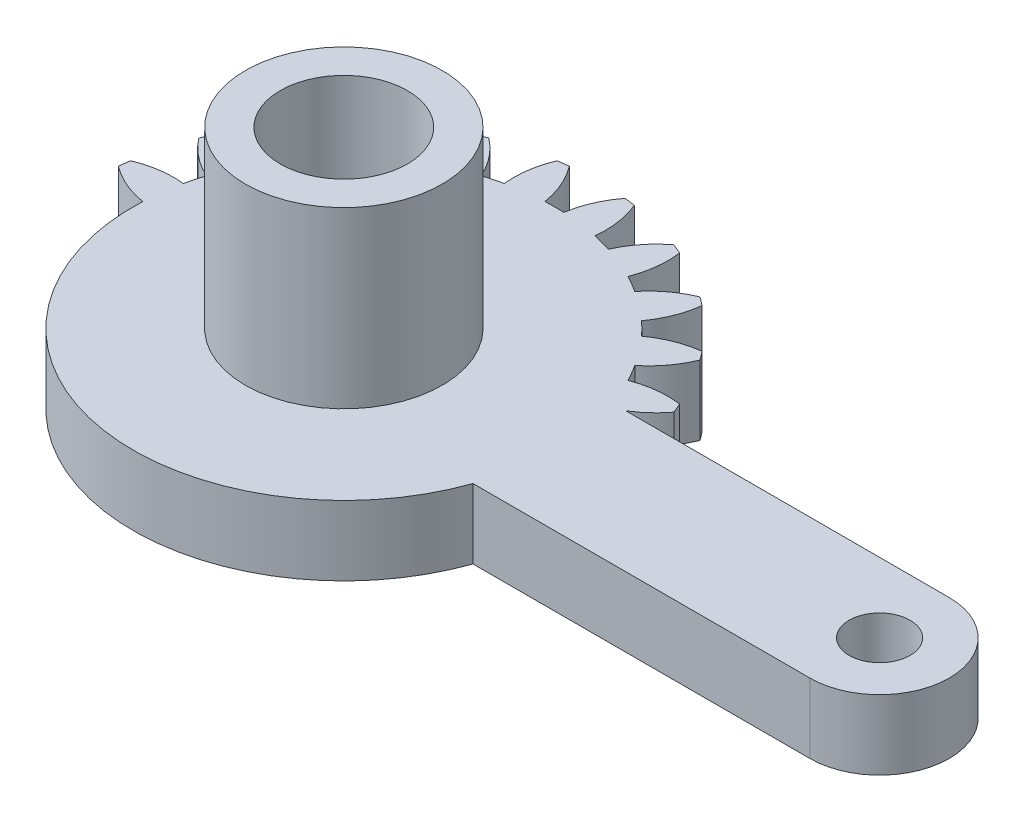
SolidWorks part; units mm, degrees
ref_plane "Front Plane" through (0, 0, 0) normal (0, 0, 1) x (1, 0, 0)
ref_plane "Top Plane" through (0, 0, 0) normal (0, 1, 0) x (1, 0, 0)
ref_plane "Right Plane" through (0, 0, 0) normal (1, 0, 0) x (0, 0, -1)
ref_plane "Plane1" through (0, 4, 0) normal (0, 1, 0) x (1, 0, 0)
sketch "Sketch1" plane through (0, 4, 0) normal (0, 1, 0) x (1, 0, 0)
  line L0 (1.3057, -4) -> (20.6437, -4)
  line L1 (20.6437, 4) -> (2.0816, 4)
  arc A0 (-24.5622, 2.2179) -> (-24.6437, 1.5991) centre (-10.1063, 0) ccw
  arc A1 (-24.6437, 1.5991) -> (-22.1869, 0.5427) centre (-21.3486, 5.8773) ccw
  arc A2 (-22.1869, 0.5427) -> (1.3057, -4) centre (-10.1063, 0) ccw
  arc A3 (20.6437, -4) -> (20.6437, 4) centre (20.6437, 0) ccw
  arc A4 (2.0816, 4) -> (3.5217, 5.3071) centre (-0.7683, 8.5867) ccw
  arc A5 (3.5217, 5.3071) -> (3.2829, 5.8838) centre (-10.1063, 0) ccw
  arc A6 (3.2829, 5.8838) -> (0.6271, 5.5703) centre (2.5684, 0.5313) ccw
  arc A7 (0.6271, 5.5703) -> (0.0844, 6.5103) centre (-10.1063, 0) ccw
  arc A8 (0.0844, 6.5103) -> (1.6838, 8.6535) centre (-3.3089, 10.711) ccw
  arc A9 (1.6838, 8.6535) -> (1.3038, 9.1487) centre (-10.1063, 0) ccw
  arc A10 (1.3038, 9.1487) -> (-1.1803, 8.1585) centre (1.999, 3.7936) ccw
  arc A11 (-1.1803, 8.1585) -> (-1.9479, 8.926) centre (-10.1063, 0) ccw
  arc A12 (-1.9479, 8.926) -> (-0.9576, 11.4102) centre (-6.3127, 12.1053) ccw
  arc A13 (-0.9576, 11.4102) -> (-1.4528, 11.7901) centre (-10.1063, 0) ccw
  arc A14 (-1.4528, 11.7901) -> (-3.596, 10.1907) centre (0.6046, 6.7975) ccw
  arc A15 (-3.596, 10.1907) -> (-4.5361, 10.7334) centre (-10.1063, 0) ccw
  arc A16 (-4.5361, 10.7334) -> (-4.2225, 13.3892) centre (-9.5751, 12.6747) ccw
  arc A17 (-4.2225, 13.3892) -> (-4.7992, 13.6281) centre (-10.1063, 0) ccw
  arc A18 (-4.7992, 13.6281) -> (-6.4554, 11.5285) centre (-1.5196, 9.3381) ccw
  arc A19 (-6.4554, 11.5285) -> (-7.5039, 11.8094) centre (-10.1063, 0) ccw
  arc A20 (-7.5039, 11.8094) -> (-7.8884, 14.4558) centre (-12.8736, 12.3803) ccw
  arc A21 (-7.8884, 14.4558) -> (-8.5072, 14.5373) centre (-10.1063, 0) ccw
  arc A22 (-8.5072, 14.5373) -> (-9.5636, 12.0806) centre (-4.2291, 11.2423) ccw
  arc A23 (-9.5636, 12.0806) -> (-10.6491, 12.0806) centre (-10.1063, 0) ccw
  arc A24 (-10.6491, 12.0806) -> (-11.7054, 14.5373) centre (-15.9836, 11.2423) ccw
  arc A25 (-11.7054, 14.5373) -> (-12.3243, 14.4558) centre (-10.1063, 0) ccw
  arc A26 (-12.3243, 14.4558) -> (-12.7088, 11.8094) centre (-7.3391, 12.3803) ccw
  arc A27 (-12.7088, 11.8094) -> (-13.7573, 11.5285) centre (-10.1063, 0) ccw
  arc A28 (-13.7573, 11.5285) -> (-15.4135, 13.6281) centre (-18.6931, 9.3381) ccw
  arc A29 (-15.4135, 13.6281) -> (-15.9901, 13.3892) centre (-10.1063, 0) ccw
  arc A30 (-15.9901, 13.3892) -> (-15.6766, 10.7334) centre (-10.6376, 12.6747) ccw
  arc A31 (-15.6766, 10.7334) -> (-16.6166, 10.1907) centre (-10.1063, 0) ccw
  arc A32 (-16.6166, 10.1907) -> (-18.7599, 11.7901) centre (-20.8173, 6.7975) ccw
  arc A33 (-18.7599, 11.7901) -> (-19.255, 11.4102) centre (-10.1063, 0) ccw
  arc A34 (-19.255, 11.4102) -> (-18.2648, 8.926) centre (-13.9, 12.1053) ccw
  arc A35 (-18.2648, 8.926) -> (-19.0324, 8.1585) centre (-10.1063, 0) ccw
  arc A36 (-19.0324, 8.1585) -> (-21.5165, 9.1487) centre (-22.2117, 3.7936) ccw
  arc A37 (-21.5165, 9.1487) -> (-21.8965, 8.6535) centre (-10.1063, 0) ccw
  arc A38 (-21.8965, 8.6535) -> (-20.2971, 6.5103) centre (-16.9038, 10.711) ccw
  arc A39 (-20.2971, 6.5103) -> (-20.8398, 5.5703) centre (-10.1063, 0) ccw
  arc A40 (-20.8398, 5.5703) -> (-23.4956, 5.8838) centre (-22.7811, 0.5313) ccw
  arc A41 (-23.4956, 5.8838) -> (-23.7344, 5.3071) centre (-10.1063, 0) ccw
  arc A42 (-23.7344, 5.3071) -> (-21.6348, 3.6509) centre (-19.4444, 8.5867) ccw
  arc A43 (-21.6348, 3.6509) -> (-21.9157, 2.6025) centre (-10.1063, 0) ccw
  arc A44 (-21.9157, 2.6025) -> (-24.5622, 2.2179) centre (-22.4867, -2.7673) ccw
  circle A45 centre (20.6437, 0) radius 1.75
  dimension "D1" = 3.5
  dimension "D4" = 5.4
  dimension "D5" = 14.625
  dimension "D6" = 4
  dimension "D7" = 5.4
  dimension "D8" = 12.0927
  dimension "D9" = 5.4
  dimension "D10" = 0.0844
  dimension "D11" = 5.4
  dimension "D12" = 0.6046
  dimension "D13" = 5.4
  dimension "D14" = 0.6271
  dimension "D15" = 5.4
  dimension "D16" = 1.3038
  dimension "D17" = 5.4
  dimension "D18" = 1.3057
  dimension "D19" = 5.4
  dimension "D20" = 1.6838
  dimension "D21" = 5.4
  dimension "D22" = 1.999
  dimension "D23" = 5.4
  dimension "D24" = 2.0816
  dimension "D25" = 5.4
  dimension "D26" = 2.5684
  dimension "D27" = 5.4
  dimension "D28" = 3.2829
  dimension "D29" = 5.4
  dimension "D30" = 3.5217
  dimension "D31" = 5.4
  dimension "D32" = 20.6437
  dimension "D33" = 5.4
  dimension "D34" = 0.9576
  dimension "D35" = 5.4
  dimension "D36" = 1.4528
  dimension "D37" = 5.4
  dimension "D38" = 1.5196
  dimension "D39" = 5.4
  dimension "D40" = 1.9479
  dimension "D41" = 5.4
  dimension "D42" = 4.2225
  dimension "D43" = 5.4
  dimension "D44" = 4.2291
  dimension "D45" = 5.4
  dimension "D46" = 4.5361
  dimension "D47" = 5.4
  dimension "D48" = 4.7992
  dimension "D49" = 7.3391
  dimension "D50" = 7.5039
  dimension "D51" = 7.8884
  dimension "D52" = 8.5072
  dimension "D53" = 10.6376
  dimension "D54" = 10.6491
  dimension "D55" = 11.7054
  dimension "D56" = 12.3243
  dimension "D57" = 13.7573
  dimension "D58" = 13.9
  dimension "D59" = 15.4135
  dimension "D60" = 15.6766
  dimension "D61" = 16.6166
  dimension "D62" = 16.9038
  dimension "D63" = 18.2648
  dimension "D64" = 18.7599
  dimension "D65" = 19.0324
  dimension "D66" = 19.4444
  dimension "D67" = 20.2971
  dimension "D68" = 20.8398
  dimension "D69" = 21.3486
  dimension "D70" = 21.5165
  dimension "D71" = 21.6348
  dimension "D72" = 21.9157
  dimension "D73" = 22.1869
  dimension "D74" = 22.4867
  dimension "D75" = 22.7811
  dimension "D76" = 0.5313
extrude "Boss-Extrude1" add sketch "Sketch1" against normal blind 4
sketch "草图1" plane through (0, 0, 0) normal (0, -1, 0) x (1, 0, 0)
  circle A0 centre (-10.1063, 0) radius 3.65
  point P6 (-10.1063, 0)
  dimension "D1" = 7.3
extrude "切除-拉伸1" cut sketch "草图1" against normal through all
sketch "草图2" plane through (0, 4, 0) normal (0, 1, 0) x (1, 0, 0)
  circle A0 centre (-10.1063, 0) radius 3.65
  circle A1 centre (-10.1063, 0) radius 5.65
  circle A2 centre (-10.1063, 0) radius 3.65 construction
  dimension "D1" = 2
extrude "凸台-拉伸1" add sketch "草图2" along normal blind 10
